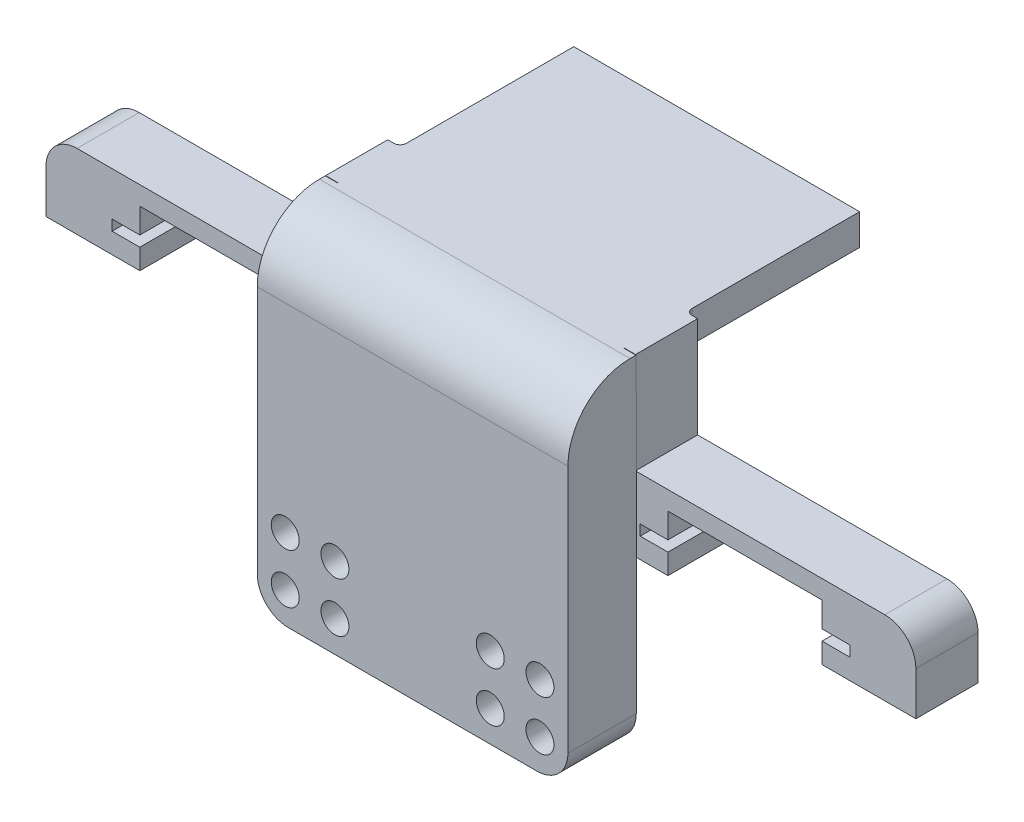
SolidWorks part; units mm, degrees
ref_plane "Front Plane" through (0, 0, 0) normal (0, 0, 1) x (1, 0, 0)
ref_plane "Top Plane" through (0, 0, 0) normal (0, 1, 0) x (1, 0, 0)
ref_plane "Right Plane" through (0, 0, 0) normal (1, 0, 0) x (0, 0, -1)
sketch "Sketch1" plane through (0, 0, 0) normal (0, 1, 0) x (1, 0, 0)
  line L0 (0, 20) -> (0, 0) construction
  line L1 (-25, 20) -> (25, 20)
  line L2 (-25, 20) -> (-25, 0.5555)
  line L4 (25, 20) -> (25, 0)
  line L5 (-25, 20) -> (0, 0) construction
  line L7 (-25, 15) -> (25, 15) construction
  line L8 (-16, 20) -> (-16, 0) construction
  line L9 (-25, 7) -> (25, 7) construction
  line L12 (0, 0) -> (25, 20) construction
  line L17 (-25, 0.5555) -> (-25, -6.9445)
  line L19 (25, 0) -> (25, -6.9445)
  line L20 (-25, -6.9445) -> (25, -6.9445)
  point P0 (0, 0)
  point P6 (-16, 20)
  point P7 (-16, 20)
  point P9 (-25, 20)
  point P11 (-25, 15)
  point P16 (-16, 15)
  point P19 (-25, 7)
  point P22 (-16, 7)
  dimension "D5" = 8
  dimension "D6" = 50
  dimension "D1" = 20
  dimension "D2" = 7.5
  dimension "D3" = 9
  dimension "D4" = 5
extrude "Boss-Extrude5" add sketch "Sketch1" along normal blind 5
sketch "Sketch3" plane through (0, 0, 0) normal (0, -1, 0) x (1, 0, 0)
  line L0 (-25, -20) -> (-25, 6.9445) construction
  line L1 (-25, 6.9445) -> (25, 6.9445) construction
  line L2 (-25, -4.0555) -> (25, -4.0555)
  line L3 (25, 6.9445) -> (25, -20) construction
  line L4 (-25, -4.0555) -> (-25, 6.9445)
  line L5 (-25, 6.9445) -> (25, 6.9445)
  line L6 (25, 6.9445) -> (25, -4.0555)
  point P0 (-25, -4.0555)
  dimension "D1" = 11
extrude "Boss-Extrude6" add sketch "Sketch3" along normal blind 50
sketch "Sketch5" plane through (0, 0, 6.9445) normal (0, 0, 1) x (1, 0, 0)
  line L0 (25, -50) -> (-25, -50) construction
  line L1 (-25, 5) -> (-25, -50) construction
  line L2 (-25, -45) -> (25, -45) construction
  line L3 (25, 5) -> (25, -50) construction
  line L4 (-20.5, -50) -> (-20.5, 5) construction
  line L5 (-25, 5) -> (25, 5) construction
  line L6 (-25, -41) -> (25, -41) construction
  line L7 (-16.5, -50) -> (-16.5, 5) construction
  line L8 (0, 5) -> (0, -50) construction
  circle A0 centre (-20.5, -45) radius 2.25
  circle A1 centre (-20.5, -37) radius 2.25
  circle A2 centre (-12.5, -45) radius 2.25
  circle A3 centre (-12.5, -37) radius 2.25
  circle A4 centre (12.5, -45) radius 2.25
  circle A5 centre (20.5, -45) radius 2.25
  circle A6 centre (12.5, -37) radius 2.25
  circle A7 centre (20.5, -37) radius 2.25
  point P0 (-20.5, -50)
  point P1 (-25, -45)
  point P16 (-25, -41)
  point P21 (-16.5, -50)
  dimension "D3" = 4
  dimension "D1" = 5
  dimension "D2" = 4.5
  dimension "D4" = 4
extrude "Cut-Extrude1" cut sketch "Sketch5" against normal blind 11
sketch "Sketch6" plane through (0, 0, -4.0555) normal (0, 0, -1) x (-1, 0, 0)
  line L0 (-25, -50) -> (-25, 0) construction
  line L1 (25, -50) -> (25, 0) construction
  line L2 (-25, -11.2088) -> (25, -11.2088)
  line L4 (-25, -21.2088) -> (25, -21.2088)
  line L6 (0, 0) -> (0, -50) construction
  line L7 (25, -50) -> (-25, -50) construction
  line L8 (60, -11.2088) -> (60, -21.2088)
  line L9 (-25, -11.2088) -> (-60, -11.2088)
  line L11 (-25, -21.2088) -> (-60, -21.2088)
  line L12 (-60, -11.2088) -> (-60, -21.2088)
  line L13 (25, -21.2088) -> (60, -21.2088)
  line L14 (25, -11.2088) -> (60, -11.2088)
  point P0 (-25, -11.2088)
  dimension "D1" = 10
  dimension "D2" = 35
extrude "Boss-Extrude8" add sketch "Sketch6" along normal blind 10
sketch "Sketch7" plane through (0, 0, -4.0555) normal (0, 0, 1) x (1, 0, 0)
  line L0 (60, -21.2088) -> (25, -21.2088) construction
  line L1 (25.6392, -19.9294) -> (60, -19.9294) construction
  line L2 (60, -11.2088) -> (60, -21.2088) construction
  line L3 (30.1, -21.2088) -> (30.1, -19.9294)
  line L4 (30.1, -19.9294) -> (25.6392, -19.9294)
  line L5 (25.6392, -19.9294) -> (25.6392, -18.2294)
  line L6 (25.6392, -18.2294) -> (30.1, -18.2294)
  line L7 (30.1, -18.2294) -> (30.1, -14.2088)
  line L8 (42.5, -11.2088) -> (42.5, -21.2088) construction
  line L9 (25, -11.2088) -> (60, -11.2088) construction
  line L10 (30.1, -14.2088) -> (54.9, -14.2088)
  line L11 (54.9, -19.9294) -> (59.3608, -19.9294)
  line L12 (59.3608, -19.9294) -> (59.3608, -18.2294)
  line L13 (59.3608, -18.2294) -> (54.9, -18.2294)
  line L14 (54.9, -18.2294) -> (54.9, -14.2088)
  line L16 (54.9, -19.9294) -> (54.9, -21.2088)
  line L17 (54.9, -21.2088) -> (30.1, -21.2088)
  line L18 (0, -2.75) -> (0, 2.75) construction
  line L19 (-25.6392, -19.9294) -> (-25.6392, -18.2294)
  line L20 (-30.1, -19.9294) -> (-25.6392, -19.9294)
  line L21 (-30.1, -21.2088) -> (-30.1, -19.9294)
  line L22 (-54.9, -21.2088) -> (-30.1, -21.2088)
  line L23 (-54.9, -19.9294) -> (-54.9, -21.2088)
  line L24 (-54.9, -19.9294) -> (-59.3608, -19.9294)
  line L25 (-59.3608, -19.9294) -> (-59.3608, -18.2294)
  line L26 (-59.3608, -18.2294) -> (-54.9, -18.2294)
  line L27 (-54.9, -18.2294) -> (-54.9, -14.2088)
  line L28 (-30.1, -14.2088) -> (-54.9, -14.2088)
  line L29 (-30.1, -18.2294) -> (-30.1, -14.2088)
  line L30 (-25.6392, -18.2294) -> (-30.1, -18.2294)
  point P0 (25, -21.2088)
  point P1 (26.6, -21.2088)
  point P3 (25.6392, -19.9294)
  point P6 (25.6392, -18.2294)
  point P7 (30.1, -21.2088)
  point P14 (26.5417, -14.6412)
  point P28 (42.5, -14.2088)
  dimension "D1" = 1.6
  dimension "D2" = 1.6
  dimension "D3" = 1.7
  dimension "D4" = 3.5
  dimension "D5" = 3.7
  dimension "D6" = 24.8
extrude "Cut-Extrude2" cut sketch "Sketch7" against normal blind 10
sketch "Sketch8" plane through (0, 5, 0) normal (0, 1, 0) x (1, 0, 0)
  line L0 (0, 0) -> (0, 14.9017) construction
  line L1 (-25, 20) -> (-23, 20)
  line L2 (-25, 20) -> (-25, 4.0068)
  line L3 (-25, 4.0068) -> (-23, 4.0068)
  line L4 (-23, 20) -> (-23, 4.0068)
  line L5 (25, 4.0068) -> (23, 4.0068)
  line L6 (23, 20) -> (23, 4.0068)
  line L7 (25, 20) -> (23, 20)
  line L8 (25, 20) -> (25, 4.0068)
  dimension "D1" = 2
extrude "Cut-Extrude3" cut sketch "Sketch8" against normal blind 5
sketch "Sketch9" plane through (-60, 0, 0) normal (-1, 0, 0) x (0, 0, 1)
  line L1 (-14.0555, -21.2088) -> (-4.0555, -21.2088)
  line L2 (-14.0555, -21.2088) -> (-14.0555, -11.2088)
  line L3 (-14.0555, -11.2088) -> (-4.0555, -11.2088)
  line L4 (-4.0555, -21.2088) -> (-4.0555, -11.2088)
extrude "Boss-Extrude9" add sketch "Sketch9" along normal blind 10
sketch "Sketch10" plane through (60, 0, 0) normal (1, 0, 0) x (0, 0, -1)
  line L1 (4.0555, -21.2088) -> (14.0555, -21.2088)
  line L2 (4.0555, -21.2088) -> (4.0555, -11.2088)
  line L3 (4.0555, -11.2088) -> (14.0555, -11.2088)
  line L4 (14.0555, -21.2088) -> (14.0555, -11.2088)
extrude "Boss-Extrude10" add sketch "Sketch10" along normal blind 10
fillet "Fillet1" radius 10 1 edges at (0, 5, 6.9445)
fillet "Fillet2" radius 5 4 edges at (25, -50, 1.4445) (-25, -50, 1.4445) (-70, -11.2088, -9.0555) (70, -11.2088, -9.0555)
sketch "Sketch11" plane through (0, -21.2088, 0) normal (0, -1, 0) x (1, 0, 0)
  line L1 (54.9, -4.0555) -> (70, -4.0555)
  line L2 (54.9, -4.0555) -> (54.9, -14.0555)
  line L3 (54.9, -14.0555) -> (70, -14.0555)
  line L4 (70, -4.0555) -> (70, -14.0555)
  line L5 (-70, -4.0555) -> (-54.9, -4.0555)
  line L6 (-70, -4.0555) -> (-70, -14.0555)
  line L7 (-70, -14.0555) -> (-54.9, -14.0555)
  line L8 (-54.9, -4.0555) -> (-54.9, -14.0555)
extrude "Boss-Extrude11" add sketch "Sketch11" along normal blind 2
sketch "Sketch12" plane through (0, -21.2088, 0) normal (0, -1, 0) x (1, 0, 0)
  line L1 (-30.1, -4.0555) -> (30.1, -4.0555)
  line L2 (-30.1, -4.0555) -> (-30.1, -14.0555)
  line L3 (-30.1, -14.0555) -> (30.1, -14.0555)
  line L4 (30.1, -4.0555) -> (30.1, -14.0555)
extrude "Boss-Extrude12" add sketch "Sketch12" along normal blind 2
sketch "Sketch14" plane through (0, -11.2088, 0) normal (0, 1, 0) x (1, 0, 0)
  line L0 (-65, 14.0555) -> (65, 14.0555) construction
  line L1 (-25, 4.0555) -> (24.8736, 4.0555)
  line L2 (-25, 4.0555) -> (-25, 14.0555)
  line L3 (-25, 14.0555) -> (24.8736, 14.0555)
  line L4 (24.8736, 4.0555) -> (24.8736, 14.0555)
extrude "Boss-Extrude14" add sketch "Sketch14" along normal up to surface (16.2088 mm away) up to face at (0, 5, -7.7673)
fillet "Fillet3" radius 1 2 edges at (23, 2.5, -14.0555) (-23, 2.5, -14.0555)
sketch "Sketch15" plane through (0, 0, -20) normal (0, 0, -1) x (-1, 0, 0)
  line L1 (-23, 5) -> (23, 5)
  line L2 (-23, 5) -> (-23, 0)
  line L3 (-23, 0) -> (23, 0)
  line L4 (23, 5) -> (23, 0)
extrude "Boss-Extrude15" add sketch "Sketch15" along normal blind 22
